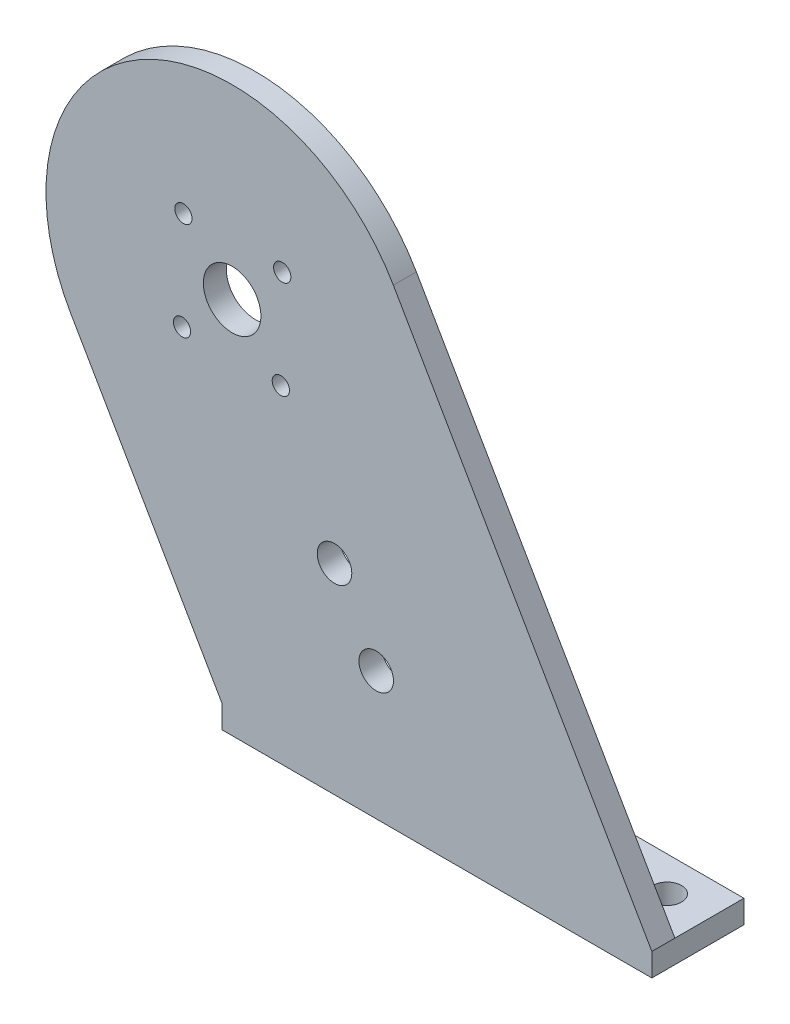
SolidWorks part; units mm, degrees
material "6061 合金"
ref_plane "前视基准面" through (0, 0, 0) normal (0, 0, 1) x (1, 0, 0)
ref_plane "上视基准面" through (0, 0, 0) normal (0, 1, 0) x (1, 0, 0)
ref_plane "右视基准面" through (0, 0, 0) normal (1, 0, 0) x (0, 0, -1)
sketch "草图1" plane through (0, 0, 0) normal (0, 0, 1) x (1, 0, 0)
  line L0 (14.2188, -45.6863) -> (-21.3543, 15.9281) construction
  line L1 (-21.3543, 15.9281) -> (-62.6788, -7.9306) construction
  line L2 (-21.3543, 15.9281) -> (16.393, 37.7216) construction
  line L3 (-21.3543, 15.9281) -> (-44.4963, 56.0111) construction
  line L4 (-49.3601, -0.241) -> (-23.1222, -45.6863)
  line L5 (6.6514, 32.0972) -> (51.5598, -45.6863)
  line L6 (-23.1222, -45.6863) -> (51.5598, -45.6863)
  line L7 (-21.3543, 15.9281) -> (-12.6495, 24.3907) construction
  line L8 (-21.3543, 15.9281) -> (-30.0592, 7.4655) construction
  line L9 (-21.3543, 15.9281) -> (-12.8917, 7.2233) construction
  line L10 (-21.3543, 15.9281) -> (-29.8169, 24.6329) construction
  line L12 (-23.1222, -45.6863) -> (51.5598, -45.6863)
  line L13 (-23.1222, -45.6863) -> (-23.1222, -49.6863)
  line L14 (-23.1222, -49.6863) -> (51.5598, -49.6863)
  line L15 (51.5598, -45.6863) -> (51.5598, -49.6863)
  arc A0 (6.6514, 32.0972) -> (-49.3601, -0.241) centre (-21.3543, 15.9281) ccw
  circle A1 centre (-21.3543, 15.9281) radius 5
  circle A2 centre (-21.3543, 15.9281) radius 12.1404 construction
  circle A3 centre (-29.8169, 24.6329) radius 1.5
  circle A4 centre (-12.6495, 24.3907) radius 1.5
  circle A5 centre (-12.8917, 7.2233) radius 1.5
  circle A6 centre (-30.0592, 7.4655) radius 1.5
  circle A7 centre (-3.5678, -14.8791) radius 3
  circle A8 centre (3.6759, -27.4255) radius 3
  point P22 (-21.3543, 15.9281)
extrude "凸台-拉伸1" add sketch "草图1" along normal blind 4 contours L15 L6 L13 L14 | L5 A0 L4 L6 A6 A5 A4 A3 A1
sketch "草图2" plane through (0, 0, 0) normal (0, 0, -1) x (-1, 0, 0)
  line L1 (-51.5598, -45.6863) -> (23.1222, -45.6863)
  line L2 (-51.5598, -45.6863) -> (-51.5598, -49.6863)
  line L3 (-51.5598, -49.6863) -> (23.1222, -49.6863)
  line L4 (23.1222, -45.6863) -> (23.1222, -49.6863)
extrude "凸台-拉伸2" add sketch "草图2" along normal blind 12
sketch "草图3" plane through (0, -45.6863, 0) normal (0, 1, 0) x (1, 0, 0)
  line L0 (-23.1222, 6) -> (51.5598, 6) construction
  line L1 (-23.1222, 12) -> (-23.1222, 0) construction
  line L2 (51.5598, 12) -> (51.5598, 0) construction
  line L3 (14.2188, 12) -> (14.2188, -8.4345) construction
  line L4 (-23.1222, 12) -> (51.5598, 12) construction
  circle A0 centre (24.2188, 6) radius 2.5
  circle A1 centre (44.2188, 6) radius 2.5
  circle A2 centre (-15.7812, 6) radius 2.5
  circle A3 centre (4.2188, 6) radius 2.5
  point P14 (14.2188, 6)
  point P17 (27.6334, 8.6303)
  dimension "D2" = 10
  dimension "D1" = 74.682
  dimension "D3" = 30
extrude "切除-拉伸1" cut sketch "草图3" against normal through all
